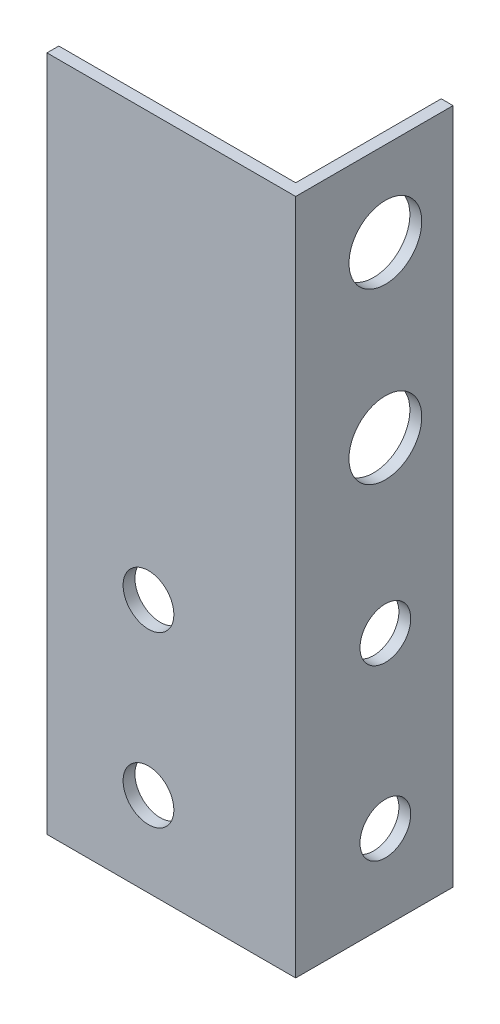
SolidWorks part; units mm, degrees
ref_plane "Front Plane" through (0, 0, 0) normal (0, 0, 1) x (1, 0, 0)
ref_plane "Top Plane" through (0, 0, 0) normal (0, 1, 0) x (1, 0, 0)
ref_plane "Right Plane" through (0, 0, 0) normal (1, 0, 0) x (0, 0, -1)
sketch "Sketch1" plane through (0, 0, 0) normal (0, 1, 0) x (1, 0, 0)
  line L0 (0, 0) -> (0, 0.7)
  line L1 (0, 0.7) -> (14, 0.7)
  line L2 (14, 0.7) -> (14, 9.3)
  line L3 (14, 9.3) -> (14.7, 9.3)
  line L4 (14.7, 9.3) -> (14.7, 0)
  line L5 (14.7, 0) -> (0, 0)
  dimension "D1" = 8.6
  dimension "D2" = 0.7
  dimension "D3" = 0.7
  dimension "D4" = 14
extrude "Boss-Extrude1" add sketch "Sketch1" along normal blind 40
sketch "Sketch2" plane through (14.7, 0, 0) normal (1, 0, 0) x (0, 0, -1)
  line L0 (5.3, 40) -> (5.3, 0) construction
  line L1 (0, 0) -> (9.3, 0) construction
  line L3 (0, 20) -> (9.3, 20) construction
  line L4 (0, 40) -> (0, 0) construction
  line L5 (9.3, 40) -> (9.3, 0) construction
  line L6 (0, 40) -> (9.3, 40) construction
  circle A0 centre (5.3, 35) radius 2.15
  circle A3 centre (5.3, 25) radius 2.15
  circle A4 centre (5.3, 15) radius 1.5
  circle A5 centre (5.3, 5) radius 1.5
  point P14 (0, 0)
  point P21 (0, 0)
  point P23 (0, 0)
  point P24 (0, 0)
  dimension "D1" = 4.3
  dimension "D7" = 3
  dimension "D2" = 4
  dimension "D3" = 5
  dimension "D4" = 10
  dimension "D5" = 10
  dimension "D6" = 10
extrude "Cut-Extrude1" cut sketch "Sketch2" against normal through all
sketch "Sketch3" plane through (0, 0, 0) normal (0, 0, 1) x (1, 0, 0)
  line L0 (6, 40) -> (6, 0) construction
  line L1 (0, 40) -> (14.7, 40) construction
  line L2 (0, 0) -> (14.7, 0) construction
  circle A0 centre (6, 15.0012) radius 1.5
  circle A1 centre (6, 5) radius 1.5
  point P12 (0, 0)
  point P13 (0, 0)
  point P14 (0, 0)
  point P15 (0, 0)
  dimension "D2" = 3
  dimension "D1" = 6
  dimension "D3" = 10.0012
  dimension "D4" = 5
extrude "Cut-Extrude2" cut sketch "Sketch3" against normal through all
